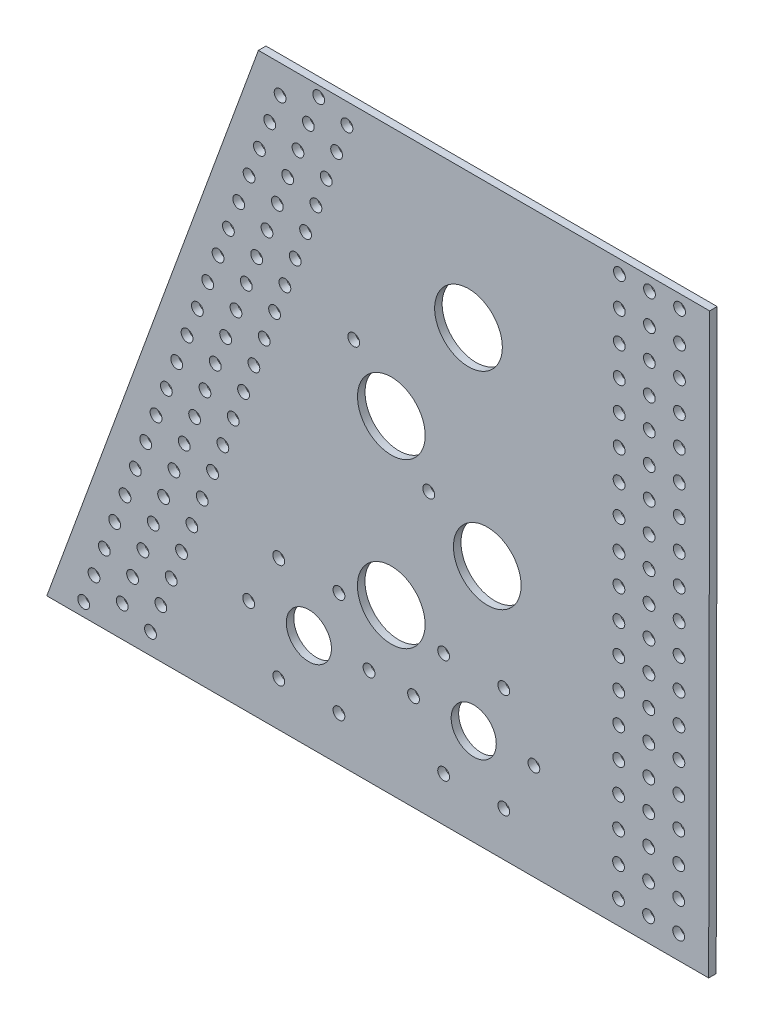
SolidWorks part; units mm, degrees
ref_plane "Front Plane" through (0, 0, 0) normal (0, 0, 1) x (1, 0, 0)
ref_plane "Top Plane" through (0, 0, 0) normal (0, 1, 0) x (1, 0, 0)
ref_plane "Right Plane" through (0, 0, 0) normal (1, 0, 0) x (0, 0, -1)
sketch "Sketch4" plane through (0, 0, 0) normal (0, 0, 1) x (1, 0, 0)
  line B0 (93.7764, 244.0959) -> (284.2764, 244.0959)
  line B1 (284.2764, 244.0959) -> (283.8532, 0)
  line B2 (283.8532, 0) -> (4.4532, 0)
  line B3 (4.4532, 0) -> (93.7764, 244.0959)
  circle B4 centre (182.4682, 187.0319) radius 14.2875
  circle B5 centre (149.9008, 138.4688) radius 14.2875
  circle B6 centre (134.0055, 158.4355) radius 2.4892
  circle B7 centre (165.6949, 118.7313) radius 2.4892
  circle B8 centre (190.3928, 103.8494) radius 14.2875
  circle B9 centre (149.8584, 69.3292) radius 14.2875
  circle B10 centre (197.3682, 18.7438) radius 2.4892
  circle B11 centre (115.0722, 40.7409) radius 9.525
  circle B12 centre (184.6682, 40.7409) radius 9.525
  circle B13 centre (210.0682, 40.7409) radius 2.4892
  circle B14 centre (171.9682, 18.7438) radius 2.4892
  circle B15 centre (159.2682, 40.7409) radius 2.4892
  circle B16 centre (171.9682, 62.7379) radius 2.4892
  circle B17 centre (197.3682, 62.7379) radius 2.4892
  circle B18 centre (140.4722, 40.7409) radius 2.4892
  circle B19 centre (127.7722, 18.7438) radius 2.4892
  circle B20 centre (102.3722, 18.7438) radius 2.4892
  circle B21 centre (89.6722, 40.7409) radius 2.4892
  circle B22 centre (102.3722, 62.7379) radius 2.4892
  circle B23 centre (127.7722, 62.7379) radius 2.4892
sketch_block_instance "Block-Gearbox_Plate1-2"
sketch_block "Block-Gearbox_Plate1" parameters "D3"=28.575, "D4"=4.9784, "D5"=4.9784, "D6"=28.575, "D7"=28.575, "D8"=28.575, "D9"=19.05, "D10"=19.05, "D11"=4.9784, "D14"=4.9784, "D1"=190.5, "D2"=279.4, "D12"=25.4, "D13"=25.4, "D15"=25.4
extrude "Boss-Extrude2" add sketch "Sketch4" along normal blind 3.175 separate body
sketch "Sketch11" plane through (0, 0, 3.175) normal (0, 0, 1) x (1, 0, 0)
  line L0 (231.6101, -832.4231) -> (318.2903, 49167.5018) construction
  line L6 (283.8532, 0) -> (284.2764, 244.0959) construction
  line L7 (284.2764, 244.0959) -> (93.7764, 244.0959) construction
  line L8 (271.5667, 238.5079) -> (258.8667, 238.5079) construction
  line L9 (271.5667, 238.5079) -> (271.5447, 225.8079) construction
  line L10 (4.4532, 0) -> (283.8532, 0) construction
  line L11 (135.8908, 211.3577) -> (-17046.5435, -46743.5564) construction
  line L12 (93.7764, 244.0959) -> (4.4532, 0) construction
  line L13 (93.7764, 244.0959) -> (47048.6904, -16938.3384) construction
  line L14 (102.9315, 232.1579) -> (114.858, 227.7936) construction
  line L15 (102.9315, 232.1579) -> (98.5671, 220.2313) construction
  line L16 (114.858, 227.7936) -> (119.2224, 239.7201) construction
  circle A0 centre (271.5667, 238.5079) radius 2.4892
  circle A1 centre (258.8667, 238.5079) radius 2.4892
  circle A2 centre (246.1667, 238.5079) radius 2.4892
  circle A3 centre (258.8447, 225.8079) radius 2.4892
  circle A4 centre (246.1447, 225.8079) radius 2.4892
  circle A5 centre (258.8227, 213.1079) radius 2.4892
  circle A6 centre (246.1227, 213.1079) radius 2.4892
  circle A7 centre (258.8006, 200.4079) radius 2.4892
  circle A8 centre (246.1006, 200.4079) radius 2.4892
  circle A9 centre (258.7786, 187.708) radius 2.4892
  circle A10 centre (246.0786, 187.708) radius 2.4892
  circle A11 centre (258.7566, 175.008) radius 2.4892
  circle A12 centre (246.0566, 175.008) radius 2.4892
  circle A13 centre (258.7346, 162.308) radius 2.4892
  circle A14 centre (246.0346, 162.308) radius 2.4892
  circle A15 centre (258.7126, 149.608) radius 2.4892
  circle A16 centre (246.0126, 149.608) radius 2.4892
  circle A17 centre (258.6906, 136.908) radius 2.4892
  circle A18 centre (245.9906, 136.908) radius 2.4892
  circle A19 centre (258.6685, 124.2081) radius 2.4892
  circle A20 centre (245.9685, 124.2081) radius 2.4892
  circle A21 centre (258.6465, 111.5081) radius 2.4892
  circle A22 centre (245.9465, 111.5081) radius 2.4892
  circle A23 centre (258.6245, 98.8081) radius 2.4892
  circle A24 centre (245.9245, 98.8081) radius 2.4892
  circle A25 centre (258.6025, 86.1081) radius 2.4892
  circle A26 centre (245.9025, 86.1081) radius 2.4892
  circle A27 centre (258.5805, 73.4081) radius 2.4892
  circle A28 centre (245.8805, 73.4081) radius 2.4892
  circle A29 centre (258.5585, 60.7082) radius 2.4892
  circle A30 centre (245.8585, 60.7082) radius 2.4892
  circle A31 centre (258.5364, 48.0082) radius 2.4892
  circle A32 centre (245.8364, 48.0082) radius 2.4892
  circle A33 centre (258.5144, 35.3082) radius 2.4892
  circle A34 centre (245.8144, 35.3082) radius 2.4892
  circle A35 centre (258.4924, 22.6082) radius 2.4892
  circle A36 centre (245.7924, 22.6082) radius 2.4892
  circle A37 centre (258.4704, 9.9082) radius 2.4892
  circle A38 centre (245.7704, 9.9082) radius 2.4892
  circle A39 centre (271.5447, 225.8079) radius 2.4892
  circle A40 centre (271.5227, 213.1079) radius 2.4892
  circle A41 centre (271.5006, 200.4079) radius 2.4892
  circle A42 centre (271.4786, 187.708) radius 2.4892
  circle A43 centre (271.4566, 175.008) radius 2.4892
  circle A44 centre (271.4346, 162.308) radius 2.4892
  circle A45 centre (271.4126, 149.608) radius 2.4892
  circle A46 centre (271.3906, 136.908) radius 2.4892
  circle A47 centre (271.3685, 124.2081) radius 2.4892
  circle A48 centre (271.3465, 111.5081) radius 2.4892
  circle A49 centre (271.3245, 98.8081) radius 2.4892
  circle A50 centre (271.3025, 86.1081) radius 2.4892
  circle A51 centre (271.2805, 73.4081) radius 2.4892
  circle A52 centre (271.2585, 60.7082) radius 2.4892
  circle A53 centre (271.2364, 48.0082) radius 2.4892
  circle A54 centre (271.2144, 35.3082) radius 2.4892
  circle A55 centre (271.1924, 22.6082) radius 2.4892
  circle A56 centre (271.1704, 9.9082) radius 2.4892
  circle A57 centre (102.9315, 232.1579) radius 2.4892
  circle A58 centre (114.858, 227.7936) radius 2.4892
  circle A59 centre (126.7846, 223.4292) radius 2.4892
  circle A60 centre (110.4937, 215.867) radius 2.4892
  circle A61 centre (122.4202, 211.5027) radius 2.4892
  circle A62 centre (106.1294, 203.9405) radius 2.4892
  circle A63 centre (118.0559, 199.5761) radius 2.4892
  circle A64 centre (101.765, 192.0139) radius 2.4892
  circle A65 centre (113.6916, 187.6496) radius 2.4892
  circle A66 centre (97.4007, 180.0874) radius 2.4892
  circle A67 centre (109.3272, 175.723) radius 2.4892
  circle A68 centre (93.0363, 168.1608) radius 2.4892
  circle A69 centre (104.9629, 163.7965) radius 2.4892
  circle A70 centre (88.672, 156.2343) radius 2.4892
  circle A71 centre (100.5985, 151.8699) radius 2.4892
  circle A72 centre (84.3077, 144.3077) radius 2.4892
  circle A73 centre (96.2342, 139.9434) radius 2.4892
  circle A74 centre (79.9433, 132.3812) radius 2.4892
  circle A75 centre (91.8699, 128.0168) radius 2.4892
  circle A76 centre (75.579, 120.4546) radius 2.4892
  circle A77 centre (87.5055, 116.0903) radius 2.4892
  circle A78 centre (71.2146, 108.5281) radius 2.4892
  circle A79 centre (83.1412, 104.1637) radius 2.4892
  circle A80 centre (66.8503, 96.6015) radius 2.4892
  circle A81 centre (78.7769, 92.2372) radius 2.4892
  circle A82 centre (62.486, 84.675) radius 2.4892
  circle A83 centre (74.4125, 80.3106) radius 2.4892
  circle A84 centre (58.1216, 72.7484) radius 2.4892
  circle A85 centre (70.0482, 68.3841) radius 2.4892
  circle A86 centre (53.7573, 60.8219) radius 2.4892
  circle A87 centre (65.6838, 56.4575) radius 2.4892
  circle A88 centre (49.393, 48.8953) radius 2.4892
  circle A89 centre (61.3195, 44.531) radius 2.4892
  circle A90 centre (45.0286, 36.9688) radius 2.4892
  circle A91 centre (56.9552, 32.6044) radius 2.4892
  circle A92 centre (40.6643, 25.0422) radius 2.4892
  circle A93 centre (52.5908, 20.6779) radius 2.4892
  circle A94 centre (36.2999, 13.1157) radius 2.4892
  circle A95 centre (48.2265, 8.7513) radius 2.4892
  circle A96 centre (31.9356, 1.1891) radius 2.4892 [skipped]
  circle A97 centre (43.8621, -3.1752) radius 2.4892 [skipped]
  circle A98 centre (98.5671, 220.2313) radius 2.4892
  circle A99 centre (94.2028, 208.3048) radius 2.4892
  circle A100 centre (89.8385, 196.3782) radius 2.4892
  circle A101 centre (85.4741, 184.4517) radius 2.4892
  circle A102 centre (81.1098, 172.5252) radius 2.4892
  circle A103 centre (76.7454, 160.5986) radius 2.4892
  circle A104 centre (72.3811, 148.6721) radius 2.4892
  circle A105 centre (68.0168, 136.7455) radius 2.4892
  circle A106 centre (63.6524, 124.819) radius 2.4892
  circle A107 centre (59.2881, 112.8924) radius 2.4892
  circle A108 centre (54.9238, 100.9659) radius 2.4892
  circle A109 centre (50.5594, 89.0393) radius 2.4892
  circle A110 centre (46.1951, 77.1128) radius 2.4892
  circle A111 centre (41.8307, 65.1862) radius 2.4892
  circle A112 centre (37.4664, 53.2597) radius 2.4892
  circle A113 centre (33.1021, 41.3331) radius 2.4892
  circle A114 centre (28.7377, 29.4066) radius 2.4892
  circle A115 centre (24.3734, 17.48) radius 2.4892
  circle A116 centre (20.0091, 5.5535) radius 2.4892
  circle A117 centre (119.2224, 239.7201) radius 2.4892
  circle A118 centre (131.1489, 235.3558) radius 2.4892
  dimension "D4" = 4.9784
  dimension "D11" = 4.9784
  dimension "D1" = 50.8
  dimension "D2" = 5.588
  dimension "D3" = 12.7
  dimension "D7" = 12.7
  dimension "D8" = 12.7
  dimension "D9" = 9.9082
  dimension "D10" = 50.8
  dimension "D12" = 11.938
  dimension "D13" = 12.7
  dimension "D16" = 12.7
  dimension "D17" = 12.7
  dimension "D18" = 5.5535
  dimension "D20" = 12.7
  dimension "D5" = 3
  dimension "D6" = 19
  dimension "D14" = 3
  dimension "D15" = 20
  dimension "D19" = 2
extrude "Cut-Extrude2" cut sketch "Sketch11" against normal blind 3.175
